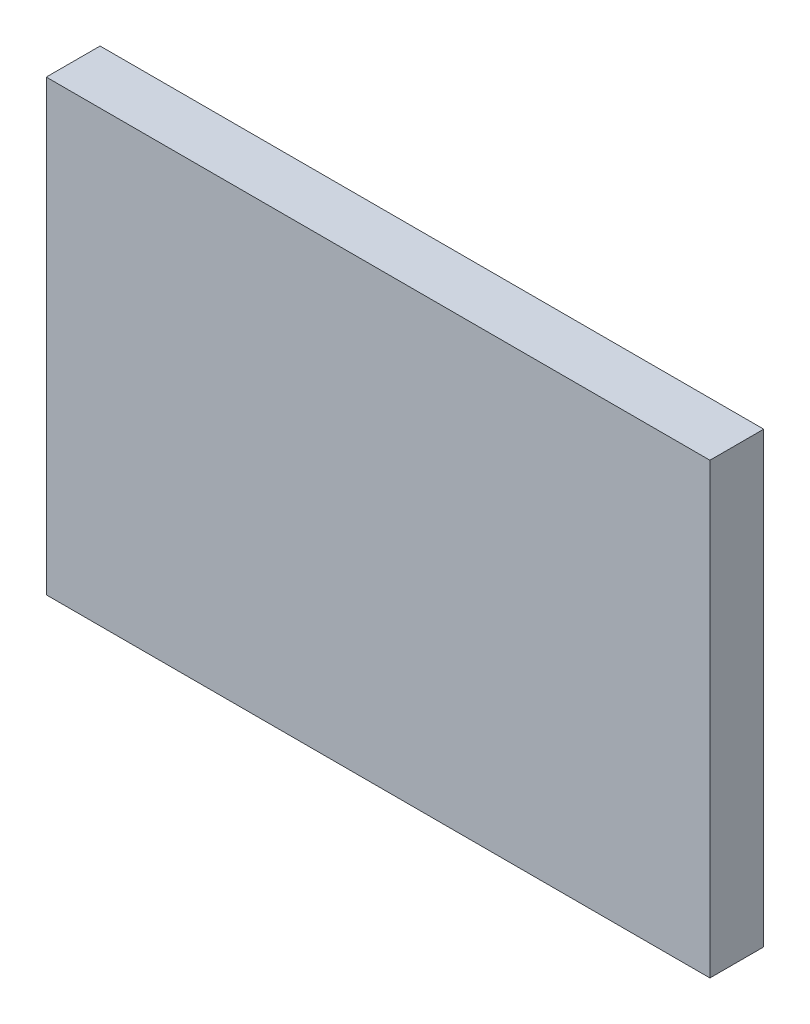
SolidWorks part; units mm, degrees
ref_plane "Front" through (0, 0, 0) normal (0, 0, 1) x (1, 0, 0)
ref_plane "Top" through (0, 0, 0) normal (0, 1, 0) x (1, 0, 0)
ref_plane "Right" through (0, 0, 0) normal (1, 0, 0) x (0, 0, -1)
sketch "Sketch1" plane through (0, 0, 0) normal (0, 0, 1) x (1, 0, 0)
  line L1 (-37, -25) -> (37, -25)
  line L2 (-37, -25) -> (-37, 25)
  line L3 (-37, 25) -> (37, 25)
  line L4 (37, -25) -> (37, 25)
  line L5 (-37, -25) -> (37, 25) construction
  line L6 (-37, 25) -> (37, -25) construction
  point P0 (0, 0)
  dimension "D1" = 74
  dimension "D2" = 50
extrude "Boss-Extrude1" add sketch "Sketch1" along normal blind 6
